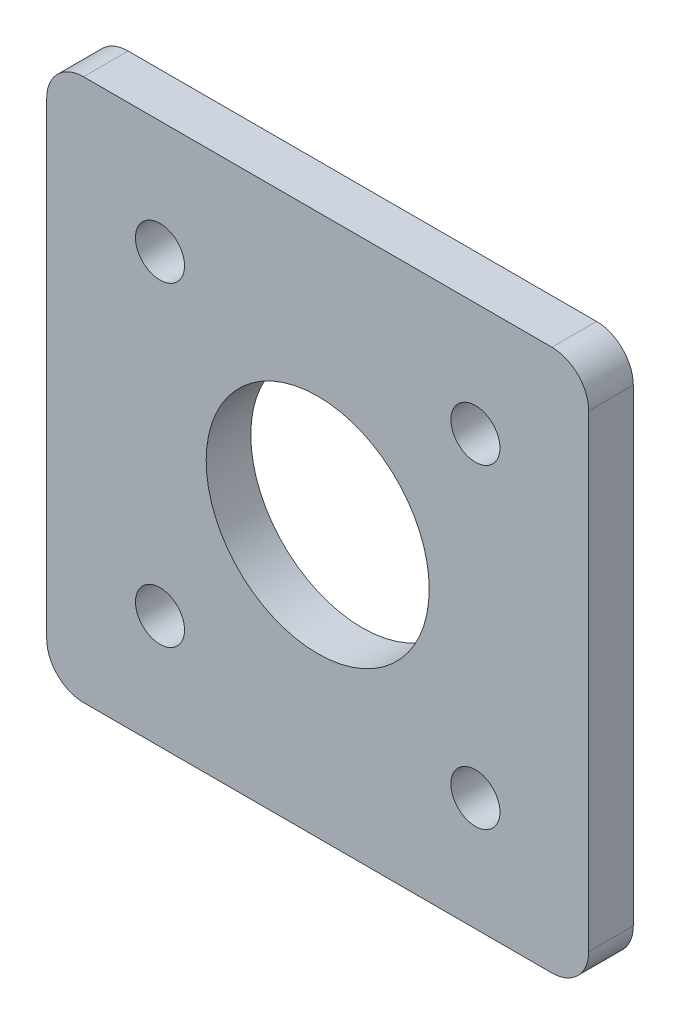
SolidWorks part; units mm, degrees
material "Thornel Mat VMA"
ref_plane "Alzado" through (0, 0, 0) normal (0, 0, 1) x (1, 0, 0)
ref_plane "Planta" through (0, 0, 0) normal (0, 1, 0) x (1, 0, 0)
ref_plane "Vista lateral" through (0, 0, 0) normal (1, 0, 0) x (0, 0, -1)
sketch "Croquis1" plane through (0, 0, 0) normal (0, 0, 1) x (1, 0, 0)
  line L4 (-18.5432, -0.9883) -> (-18.5432, -21.9883)
  line L5 (-16.5432, -23.9883) -> (4.4568, -23.9883)
  line L6 (6.4568, -21.9883) -> (6.4568, -0.9883)
  line L7 (4.4568, 1.0117) -> (-16.5432, 1.0117)
  circle A9 centre (-6.0432, -11.4883) radius 5
  arc A10 (-18.5432, -21.9883) -> (-16.5432, -23.9883) centre (-16.5432, -21.9883) ccw
  arc A11 (4.4568, -23.9883) -> (6.4568, -21.9883) centre (4.4568, -21.9883) ccw
  arc A12 (6.4568, -0.9883) -> (4.4568, 1.0117) centre (4.4568, -0.9883) ccw
  arc A13 (-16.5432, 1.0117) -> (-18.5432, -0.9883) centre (-16.5432, -0.9883) ccw
  circle A14 centre (-13.1143, -4.4173) radius 1.1
  circle A15 centre (1.0278, -4.4173) radius 1.1
  circle A16 centre (-13.1143, -18.5594) radius 1.1
  circle A17 centre (1.0278, -18.5594) radius 1.1
  dimension "D1" = 25
  dimension "D2" = 25
  dimension "D3" = 14.1421
  dimension "D4" = 14.1421
  dimension "D5" = 2.2
  dimension "D6" = 2.2
  dimension "D7" = 2.2
  dimension "D8" = 2.2
  dimension "D9" = 10
  dimension "D10" = 25
  dimension "D11" = 25
extrude "Saliente-Extruir1" add sketch "Croquis1" along normal blind 2
sketch "Croquis2" plane through (0, 0, 2) normal (0, 0, 1) x (1, 0, 0)
  line L8 (-18.1932, -0.9883) -> (-18.1932, -21.9883)
  line L9 (-16.5432, -23.6383) -> (4.4568, -23.6383)
  line L10 (6.1068, -21.9883) -> (6.1068, -0.9883)
  line L11 (4.4568, 0.6617) -> (-16.5432, 0.6617)
  line L12 (-18.1932, -0.9883) -> (-18.1932, -21.9883)
  line L13 (-16.5432, -23.6383) -> (4.4568, -23.6383)
  line L14 (6.1068, -21.9883) -> (6.1068, -0.9883)
  line L15 (4.4568, 0.6617) -> (-16.5432, 0.6617)
  line L20 (4.4568, 1.0117) -> (-16.5432, 1.0117)
  line L21 (6.4568, -21.9883) -> (6.4568, -0.9883)
  line L22 (-16.5432, -23.9883) -> (4.4568, -23.9883)
  line L23 (-18.5432, -0.9883) -> (-18.5432, -21.9883)
  line L24 (4.4568, 1.0117) -> (-16.5432, 1.0117)
  line L25 (6.4568, -21.9883) -> (6.4568, -0.9883)
  line L26 (-16.5432, -23.9883) -> (4.4568, -23.9883)
  line L27 (-18.5432, -0.9883) -> (-18.5432, -21.9883)
  arc A8 (-16.5432, 0.6617) -> (-18.1932, -0.9883) centre (-16.5432, -0.9883) ccw
  arc A9 (-18.1932, -21.9883) -> (-16.5432, -23.6383) centre (-16.5432, -21.9883) ccw
  arc A10 (4.4568, -23.6383) -> (6.1068, -21.9883) centre (4.4568, -21.9883) ccw
  arc A11 (6.1068, -0.9883) -> (4.4568, 0.6617) centre (4.4568, -0.9883) ccw
  arc A12 (-16.5432, 0.6617) -> (-18.1932, -0.9883) centre (-16.5432, -0.9883) ccw
  arc A13 (-18.1932, -21.9883) -> (-16.5432, -23.6383) centre (-16.5432, -21.9883) ccw
  arc A14 (4.4568, -23.6383) -> (6.1068, -21.9883) centre (4.4568, -21.9883) ccw
  arc A15 (6.1068, -0.9883) -> (4.4568, 0.6617) centre (4.4568, -0.9883) ccw
  arc A20 (-16.5432, 1.0117) -> (-18.5432, -0.9883) centre (-16.5432, -0.9883) ccw
  arc A21 (6.4568, -0.9883) -> (4.4568, 1.0117) centre (4.4568, -0.9883) ccw
  arc A22 (4.4568, -23.9883) -> (6.4568, -21.9883) centre (4.4568, -21.9883) ccw
  arc A23 (-18.5432, -21.9883) -> (-16.5432, -23.9883) centre (-16.5432, -21.9883) ccw
  arc A24 (-16.5432, 1.0117) -> (-18.5432, -0.9883) centre (-16.5432, -0.9883) ccw
  arc A25 (6.4568, -0.9883) -> (4.4568, 1.0117) centre (4.4568, -0.9883) ccw
  arc A26 (4.4568, -23.9883) -> (6.4568, -21.9883) centre (4.4568, -21.9883) ccw
  arc A27 (-18.5432, -21.9883) -> (-16.5432, -23.9883) centre (-16.5432, -21.9883) ccw
  dimension "D1" = 0.35
  dimension "D2" = 0
extrude "Cortar-Extruir1" cut sketch "Croquis2" against normal up to surface (2 mm away) up to face at (-6.0432, -11.4883, 0)
